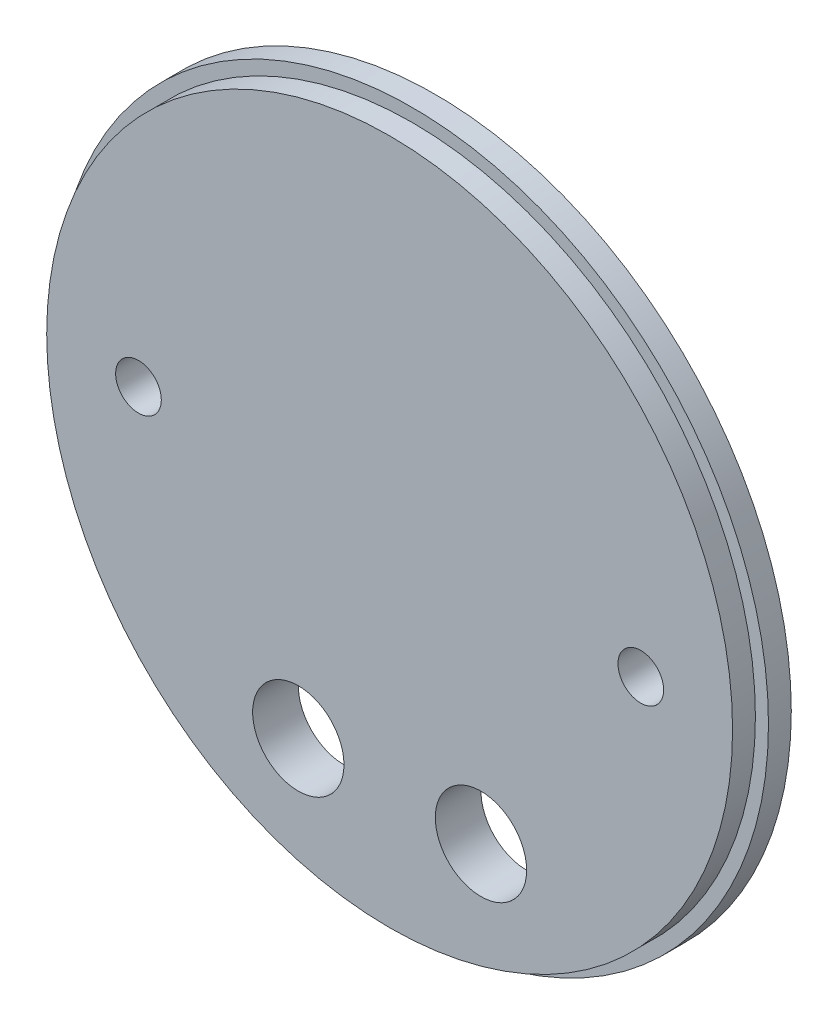
SolidWorks part; units mm, degrees
ref_plane "Front Plane" through (0, 0, 0) normal (0, 0, 1) x (1, 0, 0)
ref_plane "Top Plane" through (0, 0, 0) normal (0, 1, 0) x (1, 0, 0)
ref_plane "Right Plane" through (0, 0, 0) normal (1, 0, 0) x (0, 0, -1)
sketch "Sketch1" plane through (0, 0, 0) normal (0, 0, 1) x (1, 0, 0)
  circle A0 centre (0, 0) radius 49.5046
  dimension "D1" = 99.0092
extrude "Boss-Extrude1" add sketch "Sketch1" along normal blind 3.175
sketch "Sketch2" plane through (0, 0, 3.175) normal (0, 0, 1) x (1, 0, 0)
  circle A0 centre (0, 0) radius 47.6885
  dimension "D1" = 95.377
extrude "Boss-Extrude2" add sketch "Sketch2" along normal blind 3.175
sketch "Sketch3" plane through (0, 0, 6.35) normal (0, 0, 1) x (1, 0, 0)
  circle A0 centre (-12.7, -31.2354) radius 6.35
  circle A1 centre (12.7, -31.2354) radius 6.35
  circle A2 centre (-12.7, -31.2354) radius 12.7 construction
  circle A3 centre (-12.7, -31.2354) radius 13.97 construction
  circle A4 centre (12.7, -31.2354) radius 12.7 construction
  circle A5 centre (12.7, -31.2354) radius 13.97 construction
  circle A6 centre (0, 0) radius 47.6885 construction
  circle A7 centre (0, 0) radius 47.6885 construction
  circle A8 centre (-34.925, 0) radius 3.175
  circle A9 centre (34.925, 0) radius 3.175
  dimension "D1" = 27.94
  dimension "D2" = 25.4
  dimension "D3" = 12.7
  dimension "D4" = 6.35
  dimension "D5" = 6.35
  dimension "D6" = 69.85
  dimension "D7" = 34.925
extrude "Cut-Extrude1" cut sketch "Sketch3" against normal through all
